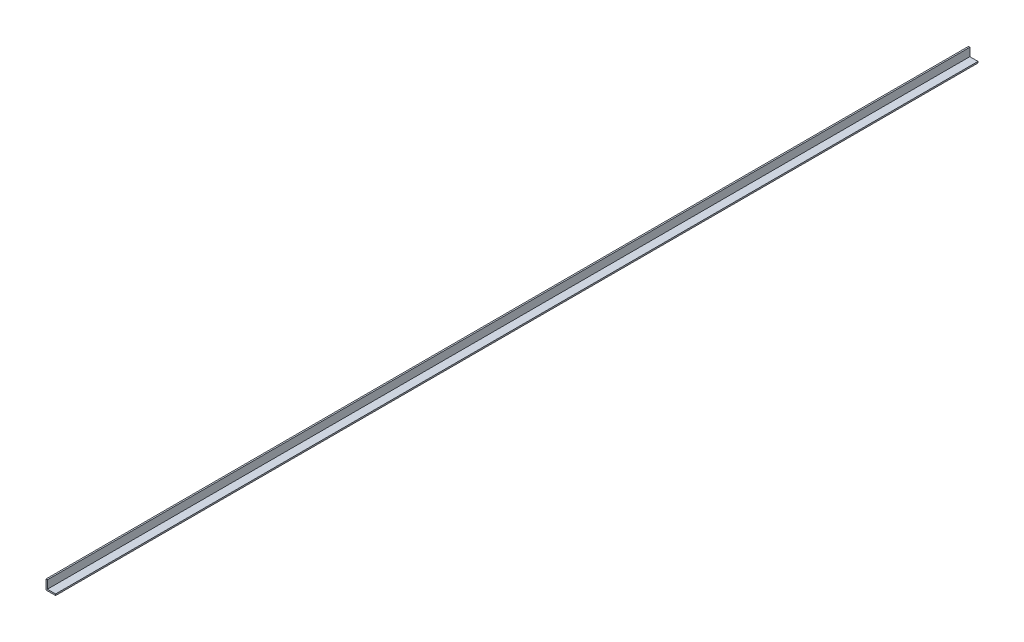
SolidWorks part; units mm, degrees
material "ASTM A36 Acero"
ref_plane "Alzado" through (0, 0, 0) normal (0, 0, 1) x (1, 0, 0)
ref_plane "Planta" through (0, 0, 0) normal (0, 1, 0) x (1, 0, 0)
ref_plane "Vista lateral" through (0, 0, 0) normal (1, 0, 0) x (0, 0, -1)
sketch "Croquis1" plane through (0, 0, 0) normal (0, 0, 1) x (1, 0, 0)
  line L0 (0, 63.5) -> (0, 0)
  line L1 (0, 0) -> (63.5, 0)
  line L2 (63.5, 0) -> (63.5, 9.53)
  line L3 (63.5, 9.53) -> (9.53, 9.53)
  line L4 (9.53, 9.53) -> (9.53, 63.5)
  line L5 (9.53, 63.5) -> (0, 63.5)
  dimension "D1" = 9.53
  dimension "D2" = 63.5
extrude "Saliente-Extruir1" add sketch "Croquis1" against normal blind 6100
